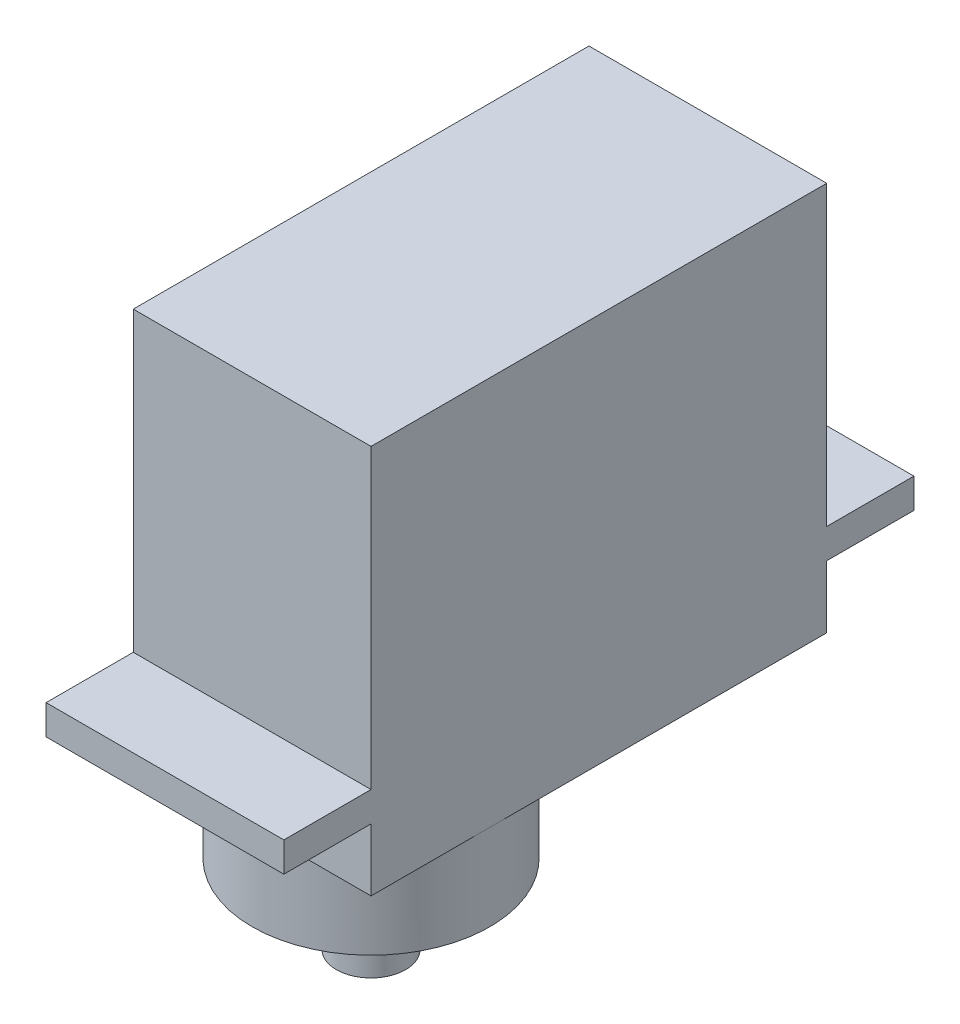
SolidWorks part; units mm, degrees
ref_plane "前视基准面" through (0, 0, 0) normal (0, 0, 1) x (1, 0, 0)
ref_plane "上视基准面" through (0, 0, 0) normal (0, 1, 0) x (1, 0, 0)
ref_plane "右视基准面" through (0, 0, 0) normal (1, 0, 0) x (0, 0, -1)
sketch "草图1" plane through (0, 0, 0) normal (1, 0, 0) x (0, 0, -1)
  line L0 (0, 0) -> (0, 15)
  line L1 (0, 15) -> (23, 15)
  line L2 (23, 15) -> (23, 0)
  line L3 (23, 0) -> (27.4, 0)
  line L4 (27.4, 0) -> (27.4, -1.5)
  line L5 (27.4, -1.5) -> (23, -1.5)
  line L6 (23, -1.5) -> (23, -4.65)
  line L7 (23, -4.65) -> (0, -4.65)
  line L8 (0, -4.65) -> (0, -1.5)
  line L9 (0, -1.5) -> (-4.4, -1.5)
  line L10 (-4.4, -1.5) -> (-4.4, 0)
  line L11 (-4.4, 0) -> (0, 0)
  dimension "D1" = 23
  dimension "D2" = 15
  dimension "D3" = 1.5
  dimension "D4" = 3.15
  dimension "D5" = 4.4
  dimension "D6" = 4.4
extrude "凸台-拉伸1" add sketch "草图1" along normal blind 12
sketch "草图2" plane through (0, -4.65, 0) normal (0, -1, 0) x (-1, 0, 0)
  line L0 (-12, 0) -> (0, 0) construction
  line L1 (-12, 0) -> (-12, 23) construction
  circle A0 centre (-6, 6) radius 6
  dimension "D1" = 12
extrude "凸台-拉伸2" add sketch "草图2" along normal blind 4.35
sketch "草图3" plane through (0, -9, 0) normal (0, -1, 0) x (1, 0, 0)
  circle A0 centre (6, -6) radius 1.75
  dimension "D1" = 3.5
extrude "凸台-拉伸3" add sketch "草图3" along normal blind 4
